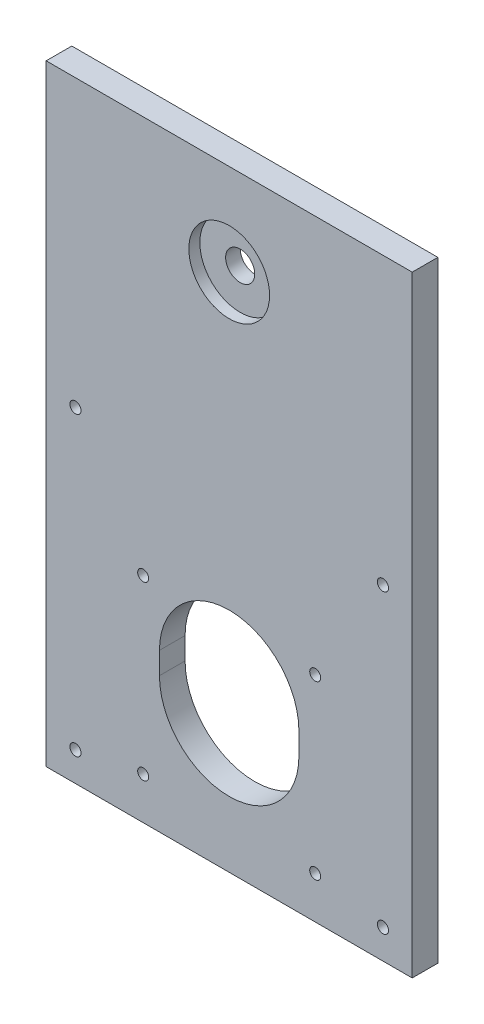
SolidWorks part; units mm, degrees
ref_plane "Front Plane" through (0, 0, 0) normal (0, 0, 1) x (1, 0, 0)
ref_plane "Top Plane" through (0, 0, 0) normal (0, 1, 0) x (1, 0, 0)
ref_plane "Right Plane" through (0, 0, 0) normal (1, 0, 0) x (0, 0, -1)
sketch "Sketch1" plane through (0, 0, 0) normal (0, 0, 1) x (1, 0, 0)
  line L1 (-50, 123.5) -> (50, 123.5)
  line L2 (-50, 123.5) -> (-50, -123.5)
  line L3 (-50, -123.5) -> (50, -123.5)
  line L4 (50, 123.5) -> (50, -123.5)
  line L5 (-50, 123.5) -> (50, -123.5) construction
  line L6 (-50, -123.5) -> (50, 123.5) construction
  line L8 (-19.05, -80.5) -> (-19.05, -86.5)
  line L9 (19.05, -86.5) -> (19.05, -80.5)
  line L10 (-23.5, -55) -> (-23.5, -65) construction
  line L14 (-22, -55) -> (-22, -65) construction
  line L15 (-25, -55) -> (-25, -65) construction
  line L16 (0, -83.5) -> (41.1398, -83.5) construction
  line L17 (0, -83.5) -> (0, -119.2312) construction
  line L18 (23.5, -55) -> (23.5, -65) construction
  line L19 (22, -55) -> (22, -65) construction
  line L20 (25, -55) -> (25, -65) construction
  line L21 (23.5, -112) -> (23.5, -102) construction
  line L22 (22, -112) -> (22, -102) construction
  line L23 (25, -112) -> (25, -102) construction
  line L24 (-23.5, -112) -> (-23.5, -102) construction
  line L25 (-22, -112) -> (-22, -102) construction
  line L26 (-25, -112) -> (-25, -102) construction
  circle A0 centre (-42, -34.5) radius 1.525
  circle A1 centre (42, -34.5) radius 1.525
  circle A2 centre (-42, -115.5) radius 1.525
  circle A3 centre (42, -115.5) radius 1.525
  arc A6 (19.05, -80.5) -> (-19.05, -80.5) centre (0, -80.5) ccw
  arc A7 (-19.05, -86.5) -> (19.05, -86.5) centre (0, -86.5) ccw
  arc A10 (-22, -55) -> (-25, -55) centre (-23.5, -55) ccw construction
  arc A11 (-25, -65) -> (-22, -65) centre (-23.5, -65) ccw construction
  arc A12 (22, -55) -> (25, -55) centre (23.5, -55) cw construction
  arc A13 (25, -65) -> (22, -65) centre (23.5, -65) cw construction
  arc A14 (22, -112) -> (25, -112) centre (23.5, -112) ccw construction
  arc A15 (25, -102) -> (22, -102) centre (23.5, -102) ccw construction
  arc A16 (-22, -112) -> (-25, -112) centre (-23.5, -112) cw construction
  arc A17 (-25, -102) -> (-22, -102) centre (-23.5, -102) cw construction
  circle A18 centre (0, 18.5) radius 3.975
  circle A19 centre (42, 115.5) radius 1.525
  circle A20 centre (-42, 115.5) radius 1.525
  circle A21 centre (-14, 32.5) radius 2.625 construction
  circle A22 centre (14, 32.5) radius 2.625 construction
  circle A23 centre (14, 4.5) radius 2.625 construction
  circle A24 centre (-14, 4.5) radius 2.625 construction
  circle A25 centre (-23.5, -65) radius 1.5
  circle A26 centre (-23.5, -112) radius 1.5
  circle A27 centre (23.5, -112) radius 1.5
  circle A28 centre (23.5, -65) radius 1.5
  point P0 (0, 0)
  point P14 (-23.5, -60)
  point P17 (0, -83.5)
  point P34 (23.5, -60)
  point P41 (23.5, -107)
  point P48 (-23.5, -107)
  dimension "D3" = 3.05
  dimension "D4" = 81
  dimension "D6" = 3
  dimension "D8" = 8
  dimension "D12" = 19.05
  dimension "D14" = 3
  dimension "D15" = 23.5
  dimension "D16" = 7.95
  dimension "D19" = 5.25
  dimension "D1" = 100
  dimension "D2" = 247
  dimension "D5" = 84
  dimension "D7" = 10
  dimension "D9" = 6
  dimension "D10" = 8
  dimension "D11" = 23.5
  dimension "D17" = 105
  dimension "D18" = 8
  dimension "D20" = 28
  dimension "D21" = 28
  dimension "D22" = 14
  dimension "D23" = 14
  dimension "D24" = 83.5
extrude "Boss-Extrude1" add sketch "Sketch1" along normal blind 7
sketch "Sketch2" plane through (0, 0, 7) normal (0, 0, 1) x (1, 0, 0)
  circle A0 centre (0, 18.5) radius 11.025
  dimension "D1" = 22.05
extrude "Cut-Extrude1" cut sketch "Sketch2" against normal blind 3
sketch "Sketch3" plane through (0, 0, 0) normal (0, 0, 1) x (1, 0, 0)
  line L0 (-23.5, -70) -> (-23.5, -60) construction
  line L1 (-26.5, -70) -> (-26.5, -60)
  line L2 (-20.5, -70) -> (-20.5, -60)
  line L3 (23.5, -70) -> (23.5, -60) construction
  line L4 (20.5, -70) -> (20.5, -60)
  line L5 (26.5, -70) -> (26.5, -60)
  line L6 (-23.5, -117) -> (-23.5, -107) construction
  line L7 (-26.5, -117) -> (-26.5, -107)
  line L8 (-20.5, -117) -> (-20.5, -107)
  line L9 (23.5, -117) -> (23.5, -107) construction
  line L10 (20.5, -117) -> (20.5, -107)
  line L11 (26.5, -117) -> (26.5, -107)
  arc A0 (-26.5, -70) -> (-20.5, -70) centre (-23.5, -70) ccw
  arc A1 (-20.5, -60) -> (-26.5, -60) centre (-23.5, -60) ccw
  arc A2 (20.5, -70) -> (26.5, -70) centre (23.5, -70) ccw
  arc A3 (26.5, -60) -> (20.5, -60) centre (23.5, -60) ccw
  arc A4 (-26.5, -117) -> (-20.5, -117) centre (-23.5, -117) ccw
  arc A5 (-20.5, -107) -> (-26.5, -107) centre (-23.5, -107) ccw
  arc A6 (20.5, -117) -> (26.5, -117) centre (23.5, -117) ccw
  arc A7 (26.5, -107) -> (20.5, -107) centre (23.5, -107) ccw
  point P4 (-23.5, -65)
  point P9 (23.5, -65)
  point P21 (-23.5, -112)
  point P29 (23.5, -112)
  dimension "D1" = 3
  dimension "D2" = 10
extrude "Cut-Extrude2" [suppressed] cut sketch "Sketch3" along normal blind 3
sketch "Sketch4" plane through (0, 0, 7) normal (0, 0, 1) x (1, 0, 0)
  line L0 (50, -123.5) -> (50, 123.5) construction
  line L1 (-50, 123.5) -> (50, 123.5)
  line L2 (-50, 123.5) -> (-50, 43.5)
  line L3 (-50, 43.5) -> (50, 43.5)
  line L4 (50, 123.5) -> (50, 43.5)
  line L5 (-50, 123.5) -> (50, 43.5) construction
  line L6 (-50, 43.5) -> (50, 123.5) construction
  line L7 (50, 123.5) -> (-50, 123.5) construction
  line L8 (-50, 123.5) -> (-50, -123.5) construction
  point P0 (0, 83.5)
  dimension "D1" = 80
extrude "Cut-Extrude3" cut sketch "Sketch4" against normal through all
